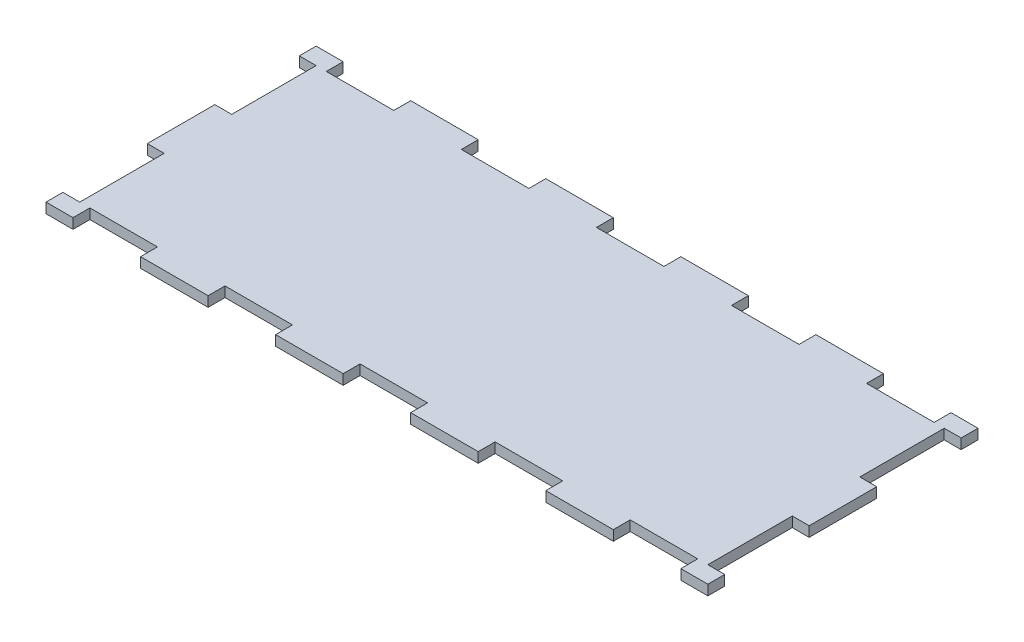
SolidWorks part; units mm, degrees
material "아크릴(내충격성)"
ref_plane "정면" through (0, 0, 0) normal (0, 0, 1) x (1, 0, 0)
ref_plane "윗면" through (0, 0, 0) normal (0, 1, 0) x (1, 0, 0)
ref_plane "우측면" through (0, 0, 0) normal (1, 0, 0) x (0, 0, -1)
sketch "스케치1" plane through (0, 0, 0) normal (0, 1, 0) x (1, 0, 0)
  line L1 (-98, 40) -> (98, 40)
  line L2 (-98, 40) -> (-98, -40)
  line L3 (-98, -40) -> (98, -40)
  line L4 (98, 40) -> (98, -40)
  line L5 (-98, 40) -> (98, -40) construction
  line L6 (-98, -40) -> (98, 40) construction
  point P0 (0, 0)
  dimension "D1" = 80
  dimension "D2" = 196
extrude "보스-돌출1" add sketch "스케치1" along normal blind 3
sketch "스케치2" plane through (0, 3, 0) normal (0, 1, 0) x (1, 0, 0)
  line L1 (-10, -40) -> (10, -40)
  line L2 (-10, -40) -> (-10, -35)
  line L3 (-10, -35) -> (10, -35)
  line L4 (10, -40) -> (10, -35)
  line L5 (0, -8.0062) -> (0, -61.9938) construction
  point P9 (0, -35)
  dimension "D1" = 5
  dimension "D2" = 20
  dimension "D3" = 35
extrude "컷-돌출1" cut sketch "스케치2" against normal up to next
pattern_linear "선형 패턴1" count 3 spacing 40 along (1, 0, 0) of "컷-돌출1"
pattern_linear "선형 패턴2" count 3 spacing 40 along (-1, 0, 0) of "컷-돌출1"
sketch "스케치3" plane through (0, 3, 0) normal (0, 1, 0) x (1, 0, 0)
  line L0 (159.7454, 0) -> (81.4326, 0) construction
  line L7 (93, -35) -> (98, -35)
  line L8 (93, -35) -> (93, -10)
  line L9 (93, -10) -> (98, -10)
  line L10 (98, -35) -> (98, -10)
  line L11 (90, -35) -> (70, -35) construction
  point P9 (120.589, 0)
  dimension "D1" = 10
  dimension "D2" = 5
  dimension "D3" = 93
extrude "컷-돌출2" cut sketch "스케치3" against normal up to next
mirror "대칭 복사2" about plane through (0, 0, 0) normal (0, 0, 1) of "선형 패턴2", "선형 패턴1", "컷-돌출1"
mirror "대칭 복사3" about plane through (0, 0, 0) normal (1, 0, 0) of "컷-돌출2"
mirror "대칭 복사5" about plane through (0, 0, 0) normal (0, 0, 1) of "대칭 복사3", "컷-돌출2"
